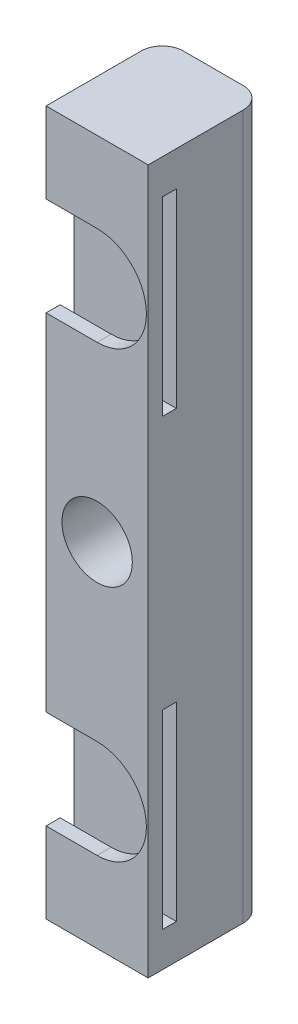
SolidWorks part; units mm, degrees
ref_plane "Front Plane" through (0, 0, 0) normal (1, 0, 0) x (0, 1, 0)
ref_plane "Top Plane" through (0, 0, 0) normal (0, 0, 1) x (0, 1, 0)
ref_plane "Right Plane" through (0, 0, 0) normal (0, 1, 0) x (-1, 0, 0)
sketch "Sketch7" plane through (0, 0, 0) normal (0, 0, 1) x (0, 1, 0)
  line L1 (-50, -7.25) -> (50, -7.25)
  line L2 (-50, -7.25) -> (-50, 7.25)
  line L3 (-50, 7.25) -> (50, 7.25)
  line L4 (50, -7.25) -> (50, 7.25)
  line L5 (-50, -7.25) -> (50, 7.25) construction
  line L6 (-50, 7.25) -> (50, -7.25) construction
  point P0 (0, 0)
  dimension "D1" = 14.5
  dimension "D2" = 100
extrude "Boss-Extrude1" add sketch "Sketch7" along normal blind 16.5
sketch "Sketch8" plane through (0, 0, 16.5) normal (0, 0, 1) x (0, -1, 0)
  circle A0 centre (0, 0) radius 5
  dimension "D1" = 10
extrude "Cut-Extrude2" cut sketch "Sketch8" against normal blind 13
sketch "Sketch9" plane through (0, 0, 16.5) normal (0, 0, 1) x (1, 0, 0)
  line L0 (0, 0) -> (0, -31.55) construction
  line L2 (-13.5, -45.05) -> (13.5, -45.05)
  line L3 (-13.5, -45.05) -> (-13.5, -18.05)
  line L4 (-13.5, -18.05) -> (13.5, -18.05)
  line L5 (13.5, -45.05) -> (13.5, -18.05)
  line L6 (-13.5, -45.05) -> (13.5, -18.05) construction
  line L7 (-13.5, -18.05) -> (13.5, -45.05) construction
  dimension "D1" = 31.55
  dimension "D2" = 27
extrude "Cut-Extrude3" cut sketch "Sketch9" against normal blind 2 from offset 2 offset against normal yes
sketch "Sketch10" plane through (0, 0, 16.5) normal (0, 0, 1) x (1, 0, 0)
  line L0 (0, 0) -> (0, -31.55) construction
  line L1 (0, -24.55) -> (-7.25, -24.55)
  line L2 (-7.25, 50) -> (-7.25, -50) construction
  line L3 (-7.25, -24.55) -> (-7.25, -38.55)
  line L4 (0, -38.55) -> (-7.25, -38.55)
  arc A0 (0, -38.55) -> (0, -24.55) centre (0, -31.55) ccw
  point P3 (0, 0)
  dimension "D2" = 14
  dimension "D1" = 31.55
extrude "Cut-Extrude4" cut sketch "Sketch10" against normal blind 2
mirror "Mirror1" about plane through (0, 0, 0) normal (0, 1, 0) of "Cut-Extrude3"
mirror "Mirror2" about plane through (0, 0, 0) normal (0, 1, 0) of "Cut-Extrude4"
fillet "Fillet1" radius 3 1 edges at (-7.25, 0, 0)
fillet "Fillet2" radius 3 1 edges at (7.25, 0, 0)
